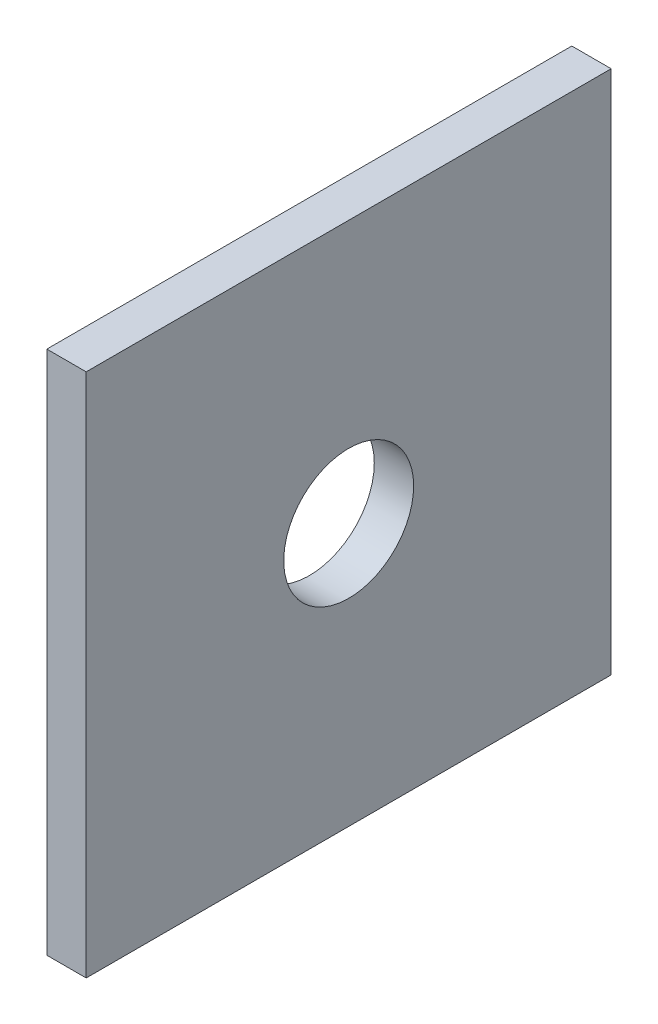
SolidWorks part; units mm, degrees
ref_plane "Front Plane" through (0, 0, 0) normal (0, 0, 1) x (1, 0, 0)
ref_plane "Top Plane" through (0, 0, 0) normal (0, 1, 0) x (1, 0, 0)
ref_plane "Right Plane" through (0, 0, 0) normal (1, 0, 0) x (0, 0, -1)
sketch "Sketch2" plane through (0, 0, 0) normal (1, 0, 0) x (0, 0, -1)
  line L1 (-20, 20) -> (20, 20)
  line L2 (-20, 20) -> (-20, -20)
  line L3 (-20, -20) -> (20, -20)
  line L4 (20, 20) -> (20, -20)
  line L5 (-20, 20) -> (20, -20) construction
  line L6 (-20, -20) -> (20, 20) construction
  point P1 (0, 0)
  dimension "D1" = 40
  dimension "D2" = 40
extrude "Boss-Extrude1" add sketch "Sketch2" along normal blind 3
sketch "Sketch3" plane through (3, 0, 0) normal (1, 0, 0) x (0, 0, -1)
  line L0 (0, 20) -> (0, -20) construction
  line L1 (20, 20) -> (-20, 20) construction
  line L2 (-20, -20) -> (20, -20) construction
  circle A0 centre (0, 0) radius 4.95
  dimension "D1" = 9.9
extrude "Cut-Extrude1" cut sketch "Sketch3" against normal blind 3
